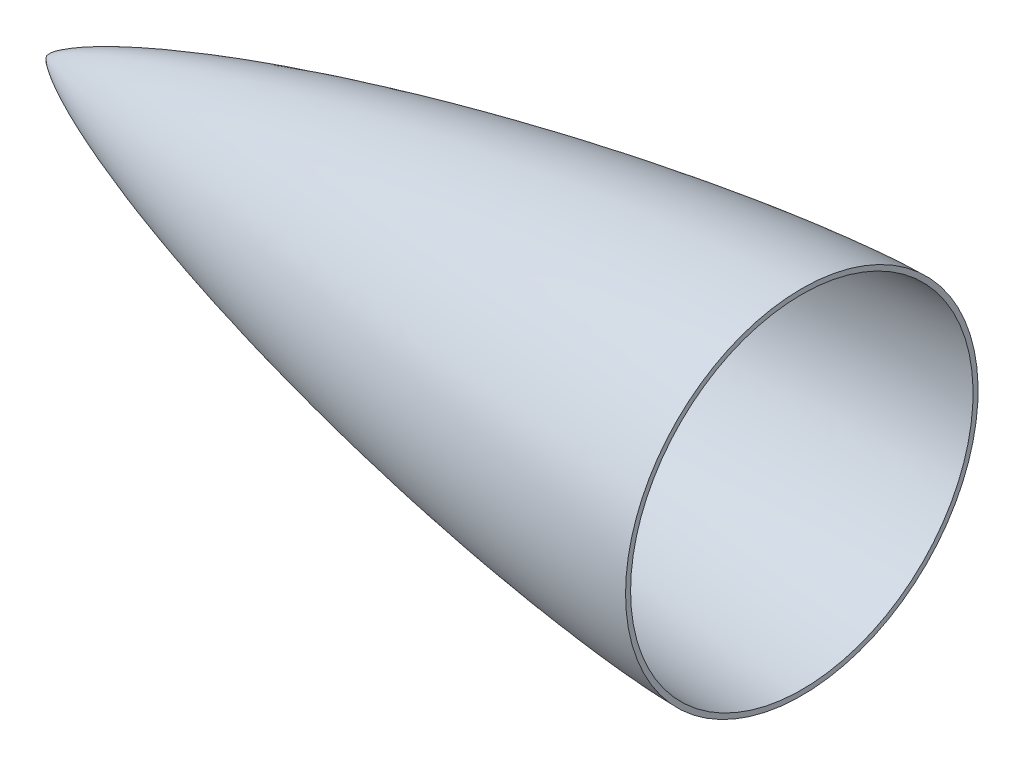
SolidWorks part; units mm, degrees
material "ABS PC"
ref_plane "Plano frontal" through (0, 0, 0) normal (0, 0, 1) x (1, 0, 0)
ref_plane "Plano superior" through (0, 0, 0) normal (0, 1, 0) x (1, 0, 0)
ref_plane "Plano direito" through (0, 0, 0) normal (1, 0, 0) x (0, 0, -1)
curve "Curva3"
  spline degree 3 poles (0, 0, 0) (0.3169, 0.3726, 0) (0.9017, 1.0604, 0) (1.9852, 1.7804, 0) (2.987, 2.4209, 0) (3.9926, 2.9985, 0) (4.9942, 3.5413, 0) (5.9956, 4.0555, 0) (6.9964, 4.5476, 0) (7.997, 5.0212, 0) (8.9974, 5.4791, 0) (9.9978, 5.9232, 0) (10.9981, 6.3553, 0) (11.9983, 6.7766, 0) (12.9984, 7.1882, 0) (13.9986, 7.5909, 0) (14.9987, 7.9854, 0) (15.9988, 8.3723, 0) (16.9989, 8.7523, 0) (17.999, 9.1257, 0) (18.9991, 9.4929, 0) (19.9991, 9.8544, 0) (20.9992, 10.2104, 0) (21.9992, 10.5612, 0) (22.9993, 10.9071, 0) (23.9993, 11.2483, 0) (24.9994, 11.585, 0) (25.9994, 11.9173, 0) (26.9994, 12.2456, 0) (27.9994, 12.5698, 0) (28.9995, 12.8903, 0) (29.9995, 13.207, 0) (30.9995, 13.5202, 0) (31.9995, 13.8299, 0) (32.9995, 14.1362, 0) (33.9996, 14.4393, 0) (34.9996, 14.7392, 0) (35.9996, 15.0361, 0) (36.9996, 15.33, 0) (37.9996, 15.6209, 0) (38.9996, 15.909, 0) (39.9996, 16.1943, 0) (40.9997, 16.4769, 0) (41.9997, 16.7568, 0) (42.9997, 17.0342, 0) (43.9997, 17.3089, 0) (44.9997, 17.5812, 0) (45.9997, 17.851, 0) (46.9997, 18.1184, 0) (47.9997, 18.3834, 0) (48.9997, 18.6461, 0) (49.9997, 18.9065, 0) (50.9997, 19.1646, 0) (51.9997, 19.4206, 0) (52.9997, 19.6743, 0) (53.9997, 19.9258, 0) (54.9998, 20.1753, 0) (55.9998, 20.4226, 0) (56.9998, 20.6678, 0) (57.9998, 20.911, 0) (58.9998, 21.1521, 0) (59.9998, 21.3913, 0) (60.9998, 21.6284, 0) (61.9998, 21.8636, 0) (62.9998, 22.0968, 0) (63.9998, 22.3281, 0) (64.9998, 22.5575, 0) (65.9998, 22.785, 0) (66.9998, 23.0105, 0) (67.9998, 23.2343, 0) (68.9998, 23.4561, 0) (69.9998, 23.6762, 0) (70.9998, 23.8943, 0) (71.9998, 24.1107, 0) (72.9998, 24.3253, 0) (73.9998, 24.538, 0) (74.9998, 24.749, 0) (75.9998, 24.9582, 0) (76.9998, 25.1656, 0) (77.9998, 25.3712, 0) (78.9998, 25.5751, 0) (79.9998, 25.7772, 0) (80.9998, 25.9776, 0) (81.9998, 26.1762, 0) (82.9998, 26.3731, 0) (83.9998, 26.5682, 0) (84.9998, 26.7617, 0) (85.9998, 26.9533, 0) (86.9998, 27.1433, 0) (87.9998, 27.3315, 0) (88.9998, 27.518, 0) (89.9998, 27.7027, 0) (90.9998, 27.8857, 0) (91.9998, 28.067, 0) (92.9998, 28.2466, 0) (93.9999, 28.4244, 0) (94.9999, 28.6005, 0) (95.9999, 28.7748, 0) (96.9999, 28.9474, 0) (97.9999, 29.1182, 0) (98.9999, 29.2873, 0) (99.9999, 29.4546, 0) (100.9999, 29.6201, 0) (101.9999, 29.7839, 0) (102.9999, 29.9458, 0) (103.9999, 30.106, 0) (104.9999, 30.2643, 0) (105.9999, 30.4209, 0) (106.9999, 30.5756, 0) (107.9999, 30.7285, 0) (108.9999, 30.8795, 0) (109.9999, 31.0286, 0) (110.9999, 31.1759, 0) (111.9999, 31.3212, 0) (112.9999, 31.4646, 0) (113.9999, 31.6061, 0) (114.9999, 31.7456, 0) (115.9999, 31.8832, 0) (116.9999, 32.0187, 0) (117.9999, 32.1522, 0) (118.9999, 32.2837, 0) (119.9999, 32.4131, 0) (120.9999, 32.5404, 0) (121.9999, 32.6655, 0) (122.9999, 32.7884, 0) (123.9999, 32.9091, 0) (124.9999, 33.0276, 0) (125.9999, 33.1438, 0) (126.9999, 33.2577, 0) (127.9999, 33.3691, 0) (128.9999, 33.4781, 0) (129.9999, 33.5847, 0) (130.9999, 33.6886, 0) (131.9999, 33.79, 0) (132.9999, 33.8886, 0) (133.9999, 33.9845, 0) (134.9999, 34.0775, 0) (135.9999, 34.1676, 0) (136.9999, 34.2546, 0) (137.9999, 34.3384, 0) (138.9999, 34.4189, 0) (139.9999, 34.4959, 0) (140.9999, 34.5693, 0) (141.9999, 34.6388, 0) (142.9999, 34.7042, 0) (143.9999, 34.7652, 0) (144.9999, 34.8214, 0) (145.9999, 34.8724, 0) (146.9999, 34.9176, 0) (147.9999, 34.9555, 0) (148.9998, 34.9869, 0) (149.6666, 34.9956, 0) (150, 35, 0) knots 0 0 0 0 0.009399 0.017347 0.024966 0.03241 0.039737 0.04698 0.054158 0.061285 0.068369 0.075417 0.082433 0.089422 0.096387 0.10333 0.110254 0.117161 0.124051 0.130926 0.137787 0.144636 0.151472 0.158298 0.165113 0.171918 0.178714 0.185501 0.19228 0.199051 0.205814 0.21257 0.219319 0.226062 0.232798 0.239528 0.246252 0.252971 0.259684 0.266392 0.273094 0.279792 0.286485 0.293173 0.299857 0.306536 0.313211 0.319882 0.326549 0.333212 0.339872 0.346527 0.353179 0.359827 0.366472 0.373113 0.379751 0.386386 0.393018 0.399646 0.406271 0.412894 0.419513 0.426129 0.432743 0.439353 0.445961 0.452567 0.459169 0.465769 0.472366 0.478961 0.485553 0.492143 0.49873 0.505315 0.511898 0.518478 0.525055 0.531631 0.538204 0.544775 0.551344 0.55791 0.564475 0.571037 0.577597 0.584155 0.59071 0.597264 0.603816 0.610366 0.616913 0.623459 0.630003 0.636544 0.643084 0.649622 0.656158 0.662692 0.669224 0.675754 0.682282 0.688809 0.695333 0.701856 0.708377 0.714896 0.721414 0.727929 0.734443 0.740955 0.747465 0.753973 0.76048 0.766985 0.773488 0.779989 0.786489 0.792986 0.799482 0.805977 0.812469 0.81896 0.82545 0.831937 0.838423 0.844907 0.851389 0.85787 0.864348 0.870826 0.877301 0.883775 0.890247 0.896717 0.903185 0.909652 0.916117 0.92258 0.929042 0.935501 0.941959 0.948416 0.95487 0.961323 0.967773 0.974222 0.98067 0.987115 0.993558 1 1 1 1
curve "Curva5"
  spline degree 3 poles (0, 0, 0) (0.3174, 0.3641, 0) (0.9043, 1.0375, 0) (1.9858, 1.7384, 0) (2.9874, 2.3638, 0) (3.9929, 2.9275, 0) (4.9944, 3.4574, 0) (5.9957, 3.9594, 0) (6.9965, 4.4398, 0) (7.9971, 4.9021, 0) (8.9975, 5.349, 0) (9.9979, 5.7826, 0) (10.9981, 6.2043, 0) (11.9983, 6.6156, 0) (12.9985, 7.0173, 0) (13.9987, 7.4103, 0) (14.9988, 7.7954, 0) (15.9989, 8.1731, 0) (16.999, 8.5439, 0) (17.999, 8.9084, 0) (18.9991, 9.2668, 0) (19.9992, 9.6196, 0) (20.9992, 9.967, 0) (21.9993, 10.3094, 0) (22.9993, 10.647, 0) (23.9993, 10.9799, 0) (24.9994, 11.3084, 0) (25.9994, 11.6328, 0) (26.9994, 11.9531, 0) (27.9995, 12.2695, 0) (28.9995, 12.5822, 0) (29.9995, 12.8912, 0) (30.9995, 13.1968, 0) (31.9995, 13.4989, 0) (32.9996, 13.7978, 0) (33.9996, 14.0935, 0) (34.9996, 14.3861, 0) (35.9996, 14.6757, 0) (36.9996, 14.9624, 0) (37.9996, 15.2462, 0) (38.9996, 15.5273, 0) (39.9997, 15.8056, 0) (40.9997, 16.0812, 0) (41.9997, 16.3543, 0) (42.9997, 16.6248, 0) (43.9997, 16.8927, 0) (44.9997, 17.1583, 0) (45.9997, 17.4214, 0) (46.9997, 17.6822, 0) (47.9997, 17.9406, 0) (48.9997, 18.1968, 0) (49.9997, 18.4507, 0) (50.9997, 18.7024, 0) (51.9997, 18.9519, 0) (52.9998, 19.1993, 0) (53.9998, 19.4446, 0) (54.9998, 19.6877, 0) (55.9998, 19.9288, 0) (56.9998, 20.1679, 0) (57.9998, 20.405, 0) (58.9998, 20.64, 0) (59.9998, 20.8731, 0) (60.9998, 21.1042, 0) (61.9998, 21.3334, 0) (62.9998, 21.5607, 0) (63.9998, 21.7861, 0) (64.9998, 22.0096, 0) (65.9998, 22.2313, 0) (66.9998, 22.4511, 0) (67.9998, 22.669, 0) (68.9998, 22.8852, 0) (69.9998, 23.0995, 0) (70.9998, 23.312, 0) (71.9998, 23.5228, 0) (72.9998, 23.7317, 0) (73.9998, 23.9389, 0) (74.9998, 24.1444, 0) (75.9998, 24.3481, 0) (76.9998, 24.55, 0) (77.9998, 24.7502, 0) (78.9998, 24.9487, 0) (79.9998, 25.1455, 0) (80.9998, 25.3405, 0) (81.9998, 25.5338, 0) (82.9998, 25.7254, 0) (83.9998, 25.9153, 0) (84.9998, 26.1035, 0) (85.9998, 26.2899, 0) (86.9998, 26.4747, 0) (87.9998, 26.6578, 0) (88.9999, 26.8391, 0) (89.9999, 27.0188, 0) (90.9999, 27.1968, 0) (91.9999, 27.373, 0) (92.9999, 27.5475, 0) (93.9999, 27.7204, 0) (94.9999, 27.8915, 0) (95.9999, 28.0609, 0) (96.9999, 28.2285, 0) (97.9999, 28.3945, 0) (98.9999, 28.5587, 0) (99.9999, 28.7211, 0) (100.9999, 28.8818, 0) (101.9999, 29.0408, 0) (102.9999, 29.198, 0) (103.9999, 29.3534, 0) (104.9999, 29.507, 0) (105.9999, 29.6588, 0) (106.9999, 29.8088, 0) (107.9999, 29.957, 0) (108.9999, 30.1034, 0) (109.9999, 30.2479, 0) (110.9999, 30.3905, 0) (111.9999, 30.5312, 0) (112.9999, 30.6701, 0) (113.9999, 30.807, 0) (114.9999, 30.9419, 0) (115.9999, 31.0749, 0) (116.9999, 31.2059, 0) (117.9999, 31.3349, 0) (118.9999, 31.4619, 0) (119.9999, 31.5867, 0) (120.9999, 31.7095, 0) (121.9999, 31.8301, 0) (122.9999, 31.9486, 0) (123.9999, 32.0648, 0) (124.9999, 32.1788, 0) (125.9999, 32.2905, 0) (126.9999, 32.3999, 0) (127.9999, 32.5068, 0) (128.9999, 32.6114, 0) (129.9999, 32.7134, 0) (130.9999, 32.8128, 0) (131.9999, 32.9096, 0) (132.9999, 33.0037, 0) (133.9999, 33.0949, 0) (134.9999, 33.1833, 0) (135.9999, 33.2687, 0) (136.9999, 33.3509, 0) (137.9999, 33.4299, 0) (138.9999, 33.5054, 0) (139.9999, 33.5774, 0) (140.9999, 33.6456, 0) (141.9999, 33.7098, 0) (142.9999, 33.7696, 0) (143.9999, 33.8248, 0) (144.9999, 33.8748, 0) (145.9999, 33.9191, 0) (146.9999, 33.9563, 0) (147.9998, 33.9872, 0) (148.6666, 33.9957, 0) (149, 34, 0) knots 0 0 0 0 0.009357 0.017305 0.024935 0.032394 0.039742 0.047008 0.054211 0.061365 0.068478 0.075555 0.082602 0.089623 0.096621 0.103597 0.110555 0.117496 0.124422 0.131333 0.13823 0.145116 0.15199 0.158853 0.165706 0.172549 0.179384 0.18621 0.193028 0.199839 0.206642 0.213438 0.220227 0.22701 0.233787 0.240559 0.247324 0.254084 0.260839 0.267588 0.274333 0.281073 0.287808 0.294539 0.301265 0.307987 0.314706 0.32142 0.32813 0.334837 0.341539 0.348238 0.354934 0.361626 0.368315 0.375001 0.381683 0.388362 0.395038 0.401711 0.408381 0.415049 0.421713 0.428374 0.435033 0.441689 0.448342 0.454993 0.461641 0.468287 0.47493 0.481571 0.488209 0.494844 0.501478 0.508109 0.514738 0.521364 0.527988 0.53461 0.54123 0.547848 0.554463 0.561076 0.567688 0.574297 0.580904 0.587509 0.594112 0.600713 0.607312 0.613909 0.620504 0.627097 0.633689 0.640278 0.646865 0.653451 0.660035 0.666617 0.673197 0.679775 0.686351 0.692926 0.699499 0.70607 0.712639 0.719207 0.725773 0.732337 0.738899 0.745459 0.752018 0.758575 0.765131 0.771684 0.778236 0.784787 0.791335 0.797882 0.804427 0.810971 0.817513 0.824053 0.830591 0.837128 0.843663 0.850197 0.856729 0.863259 0.869787 0.876314 0.882839 0.889363 0.895885 0.902405 0.908923 0.91544 0.921955 0.928468 0.93498 0.94149 0.947998 0.954504 0.961009 0.967512 0.974013 0.980513 0.98701 0.993506 1 1 1 1
sketch "Esboço6" plane through (0, 0, 0) normal (0, 0, 1) x (1, 0, 0)
  line L0 (0, 0) -> (1, 0)
  line L1 (150, 34) -> (150, 35)
  line L2 (0, 0) -> (96.27, 0) construction
  spline S1 degree 3 poles (-1366.8485, 1459.5991) (25.8091, -71.7143) (-11.3559, -7.0852) (1.9852, 1.7804) (2.987, 2.4209) (3.9926, 2.9985) (4.9942, 3.5413) (5.9956, 4.0555) (6.9964, 4.5476) (7.997, 5.0212) (8.9974, 5.4791) (9.9978, 5.9232) (10.9981, 6.3553) (11.9983, 6.7766) (12.9984, 7.1882) (13.9986, 7.5909) (14.9987, 7.9854) (15.9988, 8.3723) (16.9989, 8.7523) (17.999, 9.1257) (18.9991, 9.4929) (20.3313, 9.9745) (21.9969, 10.5629) (23.9973, 11.2498) (25.9975, 11.9188) (27.9978, 12.5712) (29.998, 13.2083) (31.9981, 13.8311) (34.3306, 14.5418) (36.9965, 15.3329) (39.9968, 16.1971) (43.3293, 17.1298) (46.9953, 18.1231) (50.6633, 19.0823) (54.3303, 20.0125) (57.3311, 20.7514) (60.6646, 21.5519) (63.9966, 22.3322) (68.3293, 23.3136) (71.6647, 24.0412) (74.6659, 24.6797) (77.9964, 25.3764) (82.9941, 26.3821) (88.6619, 27.4636) (93.6636, 28.3704) (97.9977, 29.1222) (101.6649, 29.7326) (104.9987, 30.2666) (108.3316, 30.7823) (111.9978, 31.3257) (115.665, 31.8411) (118.9988, 32.2863) (121.9988, 32.6682) (124.9988, 33.0306) (127.6658, 33.3343) (129.9995, 33.5859) (131.9995, 33.7913) (133.9995, 33.9859) (135.9995, 34.1691) (137.6664, 34.3116) (139.333, 34.4457) (140.6663, 34.5461) (141.9999, 34.6388) (142.9999, 34.7042) (143.9999, 34.7652) (144.9999, 34.8214) (145.9999, 34.8724) (146.9999, 34.9176) (147.9999, 34.9555) (177.9294, 35.8959) (208.036, 12.7437) (194.4702, 2033.7517) knots -0.282438 -0.282438 -0.282438 -0.282438 0.009399 0.017347 0.024966 0.03241 0.039737 0.04698 0.054158 0.061285 0.068369 0.075417 0.082433 0.089422 0.096387 0.10333 0.110254 0.117161 0.124051 0.130926 0.137787 0.144636 0.158298 0.171918 0.185501 0.199051 0.21257 0.226062 0.239528 0.259684 0.279792 0.299857 0.326549 0.353179 0.373113 0.399646 0.412894 0.439353 0.465769 0.49873 0.505315 0.525055 0.564475 0.603816 0.636544 0.662692 0.688809 0.708377 0.727929 0.753973 0.779989 0.799482 0.81896 0.838423 0.85787 0.870826 0.883775 0.896717 0.909652 0.92258 0.929042 0.941959 0.948416 0.95487 0.961323 0.967773 0.974222 0.98067 0.987115 0.993558 1.559232 1.559232 1.559232 1.559232 only from (0, 0) to (150, 35) construction
  spline S2 degree 3 poles (1, 0) (1.3174, 0.3641) (1.9043, 1.0375) (2.9858, 1.7384) (3.9874, 2.3638) (4.9929, 2.9275) (5.9944, 3.4574) (6.9957, 3.9594) (7.9965, 4.4398) (8.9971, 4.9021) (9.9975, 5.349) (10.9979, 5.7826) (11.9981, 6.2043) (12.9983, 6.6156) (13.9985, 7.0173) (14.9987, 7.4103) (15.9988, 7.7954) (16.9989, 8.1731) (17.999, 8.5439) (18.999, 8.9084) (20.3313, 9.3859) (21.9969, 9.9688) (23.9972, 10.6486) (25.9975, 11.3099) (27.9978, 11.9545) (29.9979, 12.5835) (31.9981, 13.198) (34.3306, 13.8989) (36.9965, 14.6787) (39.9968, 15.5301) (42.9971, 16.357) (45.9973, 17.1609) (48.9975, 17.9431) (51.9977, 18.7048) (55.3304, 19.5292) (58.6639, 20.3293) (62.3307, 21.1839) (65.6642, 21.9383) (69.331, 22.7442) (72.9971, 23.5267) (76.9973, 24.3519) (80.9974, 25.1493) (85.3302, 25.9831) (89.9963, 26.8453) (94.331, 27.6093) (97.9987, 28.2306) (101.3316, 28.7779) (104.3321, 29.2523) (107.9983, 29.8122) (111.3312, 30.3001) (114.9988, 30.8094) (117.6658, 31.1642) (119.9995, 31.4628) (122.3325, 31.7518) (124.6659, 32.0283) (126.9995, 32.2917) (128.9995, 32.508) (130.9995, 32.7146) (132.9995, 32.9109) (134.9995, 33.0964) (136.9995, 33.2702) (138.6664, 33.4047) (139.9999, 33.5054) (140.9999, 33.5774) (141.9999, 33.6456) (142.9999, 33.7098) (143.9999, 33.7696) (144.9999, 33.8248) (145.9999, 33.8748) (146.9999, 33.9191) (147.9999, 33.9563) (148.9998, 33.9872) (149.6666, 33.9957) (150, 34) knots 0 0 0 0 0.009357 0.017305 0.024935 0.032394 0.039742 0.047008 0.054211 0.061365 0.068478 0.075555 0.082602 0.089623 0.096621 0.103597 0.110555 0.117496 0.124422 0.131333 0.13823 0.15199 0.165706 0.179384 0.193028 0.206642 0.220227 0.233787 0.254084 0.274333 0.294539 0.314706 0.334837 0.354934 0.375001 0.401711 0.421713 0.448342 0.468287 0.494844 0.521364 0.547848 0.574297 0.607312 0.640278 0.660035 0.679775 0.70607 0.719207 0.752018 0.771684 0.791335 0.804427 0.817513 0.837128 0.850197 0.863259 0.876314 0.889363 0.902405 0.91544 0.928468 0.93498 0.94149 0.947998 0.954504 0.961009 0.967512 0.974013 0.980513 0.98701 0.993506 1 1 1 1
  spline S3 degree 3 poles (0, 0) (0.3169, 0.3726) (0.9017, 1.0604) (1.9852, 1.7804) (2.987, 2.4209) (3.9926, 2.9985) (4.9942, 3.5413) (5.9956, 4.0555) (6.9964, 4.5476) (7.997, 5.0212) (8.9974, 5.4791) (9.9978, 5.9232) (10.9981, 6.3553) (11.9983, 6.7766) (12.9984, 7.1882) (13.9986, 7.5909) (14.9987, 7.9854) (15.9988, 8.3723) (16.9989, 8.7523) (17.999, 9.1257) (18.9991, 9.4929) (20.3313, 9.9745) (21.9969, 10.5629) (23.9973, 11.2498) (25.9975, 11.9188) (27.9978, 12.5712) (29.998, 13.2083) (31.9981, 13.8311) (34.3306, 14.5418) (36.9965, 15.3329) (39.9968, 16.1971) (43.3293, 17.1298) (46.9953, 18.1231) (50.6633, 19.0823) (54.3303, 20.0125) (57.3311, 20.7514) (60.6646, 21.5519) (63.9966, 22.3322) (68.3293, 23.3136) (71.6647, 24.0412) (74.6659, 24.6797) (77.9964, 25.3764) (82.9941, 26.3821) (88.6619, 27.4636) (93.6636, 28.3704) (97.9977, 29.1222) (101.6649, 29.7326) (104.9987, 30.2666) (108.3316, 30.7823) (111.9978, 31.3257) (115.665, 31.8411) (118.9988, 32.2863) (121.9988, 32.6682) (124.9988, 33.0306) (127.6658, 33.3343) (129.9995, 33.5859) (131.9995, 33.7913) (133.9995, 33.9859) (135.9995, 34.1691) (137.6664, 34.3116) (139.333, 34.4457) (140.6663, 34.5461) (141.9999, 34.6388) (142.9999, 34.7042) (143.9999, 34.7652) (144.9999, 34.8214) (145.9999, 34.8724) (146.9999, 34.9176) (147.9999, 34.9555) (148.9998, 34.9869) (149.6666, 34.9956) (150, 35) knots 0 0 0 0 0.009399 0.017347 0.024966 0.03241 0.039737 0.04698 0.054158 0.061285 0.068369 0.075417 0.082433 0.089422 0.096387 0.10333 0.110254 0.117161 0.124051 0.130926 0.137787 0.144636 0.158298 0.171918 0.185501 0.199051 0.21257 0.226062 0.239528 0.259684 0.279792 0.299857 0.326549 0.353179 0.373113 0.399646 0.412894 0.439353 0.465769 0.49873 0.505315 0.525055 0.564475 0.603816 0.636544 0.662692 0.688809 0.708377 0.727929 0.753973 0.779989 0.799482 0.81896 0.838423 0.85787 0.870826 0.883775 0.896717 0.909652 0.92258 0.929042 0.941959 0.948416 0.95487 0.961323 0.967773 0.974222 0.98067 0.987115 0.993558 1 1 1 1
revolve "Revolução6" add sketch "Esboço6" angle 360 about L2
